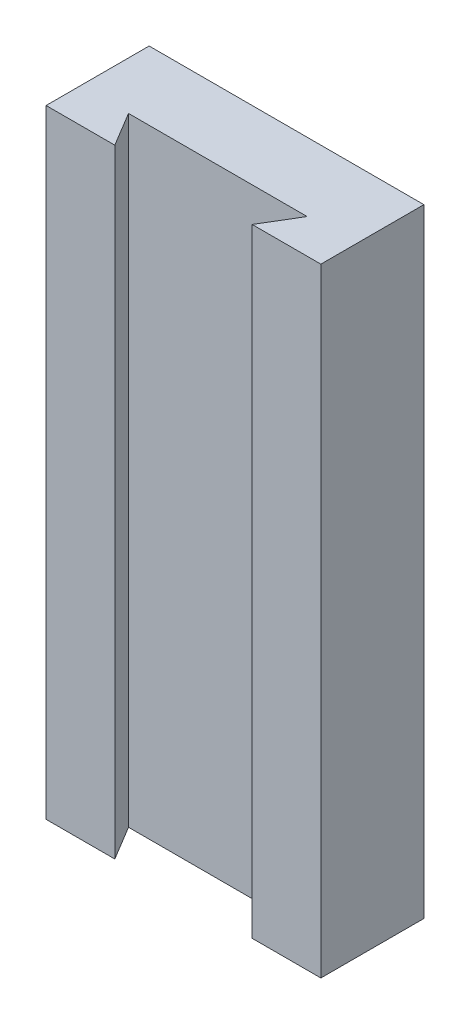
SolidWorks part; units mm, degrees
ref_plane "前视基准面" through (0, 0, 0) normal (0, 0, 1) x (1, 0, 0)
ref_plane "上视基准面" through (0, 0, 0) normal (0, 1, 0) x (1, 0, 0)
ref_plane "右视基准面" through (0, 0, 0) normal (1, 0, 0) x (0, 0, -1)
other "Configuration Table"
sketch "草图1" plane through (0, 0, 0) normal (0, 0, 1) x (1, 0, 0)
  line L1 (0, 0) -> (40, 0)
  line L2 (0, 0) -> (0, -90)
  line L3 (0, -90) -> (40, -90)
  line L4 (40, 0) -> (40, -90)
  dimension "D1" = 40
  dimension "D2" = 90
extrude "凸台-拉伸1" add sketch "草图1" along normal blind 15
sketch "草图2" plane through (0, -90, 0) normal (0, -1, 0) x (1, 0, 0)
  line L0 (10, 15) -> (7, 10)
  line L1 (0, 15) -> (40, 15) construction
  line L2 (7, 10) -> (33, 10)
  line L3 (33, 10) -> (30, 15)
  line L5 (20, 15) -> (20, 0) construction
  line L6 (0, 0) -> (40, 0) construction
  line L7 (10, 15) -> (30, 15)
  dimension "D1" = 26
  dimension "D2" = 5
  dimension "D3" = 13
  dimension "D4" = 10
  dimension "D5" = 10
extrude "切除-拉伸1" cut sketch "草图2" against normal through all
